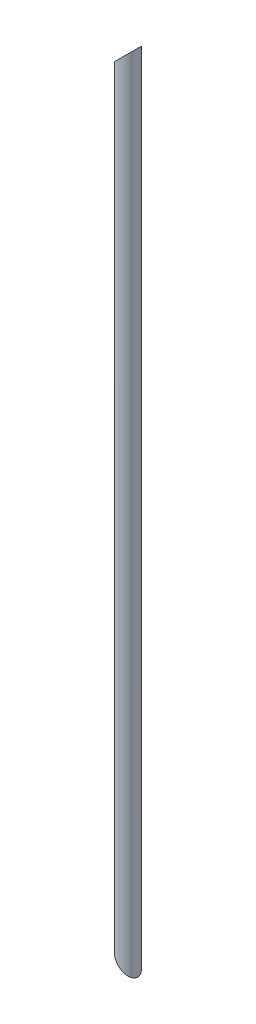
SolidWorks part; units mm, degrees
ref_plane "Plano frontal" through (0, 0, 0) normal (0, 0, 1) x (1, 0, 0)
ref_plane "Plano superior" through (0, 0, 0) normal (0, 1, 0) x (1, 0, 0)
ref_plane "Plano direito" through (0, 0, 0) normal (1, 0, 0) x (0, 0, -1)
sketch "Esboço2" plane through (0, 0, 0) normal (0, 0, 1) x (1, 0, 0)
  line L0 (0, 0) -> (0, 2650) construction
  line L1 (31.75, 0) -> (31.75, 2650)
  line L2 (31.75, 2650) -> (0, 2650)
  line L3 (31.75, 0) -> (0, 0)
  line L4 (0, 0) -> (0, 2650)
  dimension "D1" = 31.75
  dimension "D2" = 2650
revolve "Revolução2" add sketch "Esboço2" angle 360 about L0
sketch "Esboço3" plane through (0, 0, 0) normal (0, 0, 1) x (1, 0, 0)
  line L0 (-31.75, 2650) -> (31.75, 2650)
  line L1 (31.75, 2650) -> (-31.75, 2586.5)
  line L2 (-31.75, 2650) -> (-31.75, 0) construction
  line L3 (-31.75, 2586.5) -> (-31.75, 2650)
  line L4 (31.75, 0) -> (-31.75, 63.5)
  line L8 (-31.75, 63.5) -> (-31.75, 0)
  line L9 (-31.75, 0) -> (31.75, 0)
extrude "Corte-extrusão1" cut sketch "Esboço3" against normal through all both and the other way through all
sketch "Esboço9" plane through (0, 0, 0) normal (0, 1, 0) x (1, 0, 0)
  circle A0 centre (0, 0) radius 30.75
  dimension "D1" = 61.5
extrude "Corte-extrusão6" cut sketch "Esboço9" along normal through all
sketch "Esboço10" plane through (15.875, 15.875, 0) normal (-0.7071, -0.7071, 0) x (0, 0, 1)
  line L0 (0, 67.3519) -> (0, -22.4506) construction
  ellipse E0 centre (0, 22.4506) end of major axis (0, 67.3519) minor radius 31.75 construction
  point P9 (0, 22.4506)
